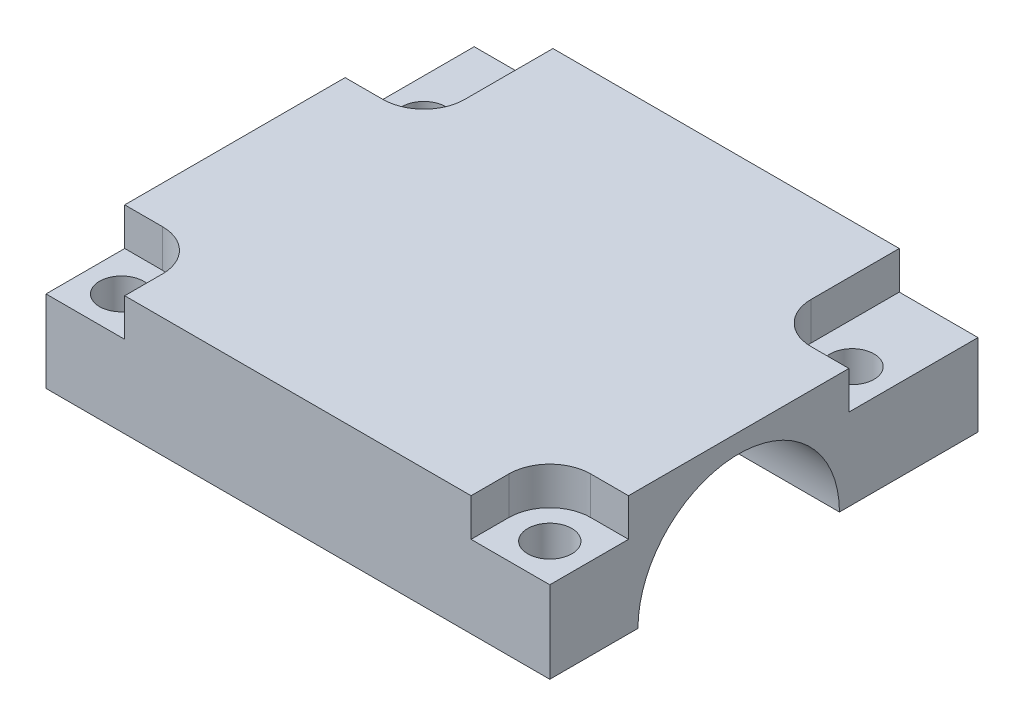
SolidWorks part; units mm, degrees
material "ABS"
ref_plane "Front Plane" through (0, 0, 0) normal (0, 0, 1) x (1, 0, 0)
ref_plane "Top Plane" through (0, 0, 0) normal (0, 1, 0) x (1, 0, 0)
ref_plane "Right Plane" through (0, 0, 0) normal (1, 0, 0) x (0, 0, -1)
sketch "Sketch1" plane through (0, 0, 0) normal (0, 1, 0) x (1, 0, 0)
  line L1 (-17, -12) -> (17, -12) construction
  line L2 (-17, -12) -> (-17, 12) construction
  line L3 (-17, 12) -> (17, 12) construction
  line L4 (17, -12) -> (17, 12) construction
  line L5 (-17, -12) -> (17, 12) construction
  line L6 (-17, 12) -> (17, -12) construction
  line L7 (-20, -15) -> (20, -15)
  line L8 (-20, -15) -> (-20, 19)
  line L9 (-20, 19) -> (20, 19)
  line L10 (20, -15) -> (20, 19)
  circle A0 centre (-17, 12) radius 1.75
  circle A1 centre (17, 12) radius 1.75
  circle A2 centre (17, -12) radius 1.75
  circle A3 centre (-17, -12) radius 1.75
  point P0 (0, 0)
  point P10 (0, 0)
  dimension "D1" = 3.5
  dimension "D6" = 3
  dimension "D7" = 7
  dimension "D2" = 34
  dimension "D3" = 24
  dimension "D5" = 40
extrude "Boss-Extrude1" add sketch "Sketch1" along normal blind 9.5
sketch "Sketch2" plane through (20, 0, 0) normal (1, 0, 0) x (0, 0, -1)
  line L2 (-15, 9.5) -> (-15, 0) construction
  circle A0 centre (0, 0) radius 8
  dimension "D1" = 16
  dimension "D2" = 15
extrude "Cut-Extrude1" cut sketch "Sketch2" against normal through all
sketch "Sketch3" plane through (0, 9.5, 0) normal (0, 1, 0) x (1, 0, 0)
  line L0 (-17, -8.75) -> (-20, -8.75)
  line L1 (-20, 19) -> (-20, -15) construction
  line L2 (-20, -8.75) -> (-20, -15)
  line L3 (-20, -15) -> (-13.75, -15)
  line L4 (-20, -15) -> (20, -15) construction
  line L5 (-13.75, -15) -> (-13.75, -12)
  arc A0 (-13.75, -12) -> (-17, -8.75) centre (-17, -12) ccw
  dimension "D1" = 6.5
extrude "Cut-Extrude2" cut sketch "Sketch3" against normal blind 3
mirror "Mirror1" about plane through (0, 0, 0) normal (1, 0, 0) of "Cut-Extrude2"
mirror "Mirror2" about plane through (0, 0, 0) normal (0, 0, 1) of "Mirror1", "Cut-Extrude2"
sketch "Sketch4" plane through (0, 9.5, 0) normal (0, 1, 0) x (1, 0, 0)
  line L1 (-20, 19) -> (-13.75, 19)
  line L2 (-20, 19) -> (-20, 15)
  line L3 (-20, 15) -> (-13.75, 15)
  line L4 (-13.75, 19) -> (-13.75, 15)
  line L5 (20, 19) -> (13.75, 19)
  line L6 (20, 19) -> (20, 15)
  line L7 (20, 15) -> (13.75, 15)
  line L8 (13.75, 19) -> (13.75, 15)
extrude "Cut-Extrude3" cut sketch "Sketch4" against normal up to surface (3 mm away) up to face at (17, 6.5, -10.25)
